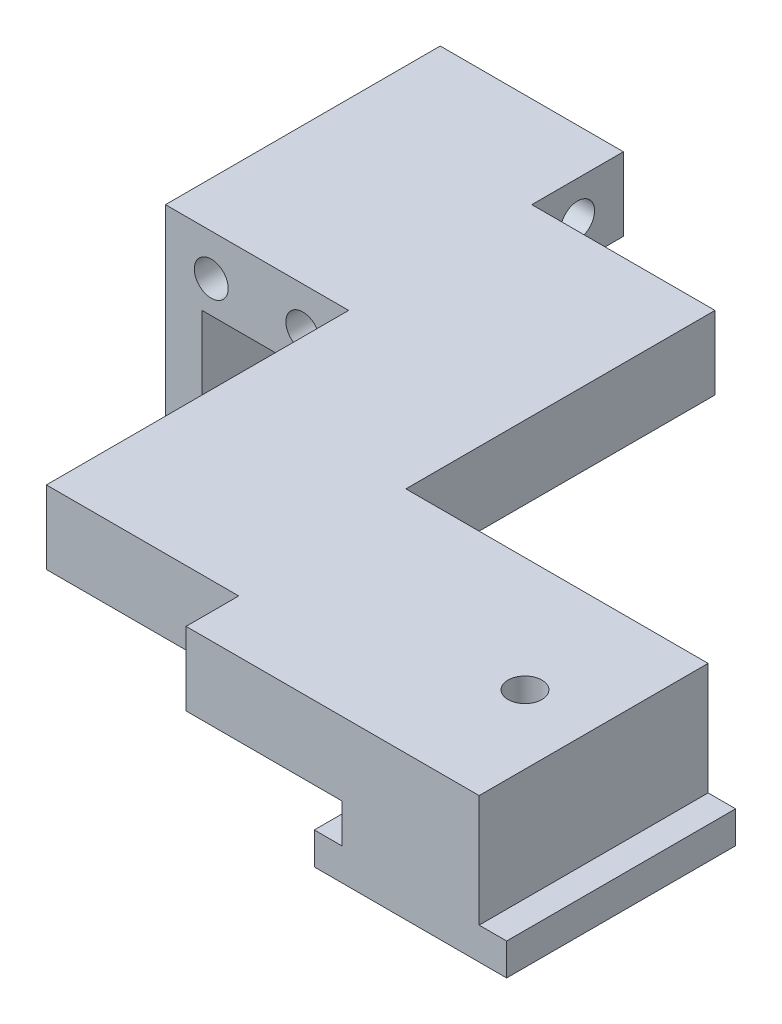
SolidWorks part; units mm, degrees
ref_plane "Front Plane" through (0, 0, 0) normal (0, 0, 1) x (1, 0, 0)
ref_plane "Top Plane" through (0, 0, 0) normal (0, 1, 0) x (1, 0, 0)
ref_plane "Right Plane" through (0, 0, 0) normal (1, 0, 0) x (0, 0, -1)
sketch "Sketch1" plane through (0, 0, 0) normal (0, 0, 1) x (1, 0, 0)
  line L0 (-10.5, 0) -> (10.5, 0)
  line L1 (10.5, 0) -> (10.5, 3.5)
  line L2 (10.5, 3.5) -> (7.5, 3.5)
  line L3 (7.5, 3.5) -> (7.5, 15.75)
  line L4 (7.5, 15.75) -> (-7.5, 15.75)
  line L5 (-7.5, 15.75) -> (-7.5, 3.5)
  line L6 (-7.5, 3.5) -> (-10.5, 3.5)
  line L7 (-10.5, 3.5) -> (-10.5, 0)
  dimension "D1" = 21
  dimension "D2" = 3.5
  dimension "D3" = 3
  dimension "D4" = 12.25
extrude "Boss-Extrude1" add sketch "Sketch1" along normal mid plane 25
sketch "Sketch2" plane through (-7.5, 0, 0) normal (-1, 0, 0) x (0, 0, 1)
  line L0 (12.5, 15.75) -> (12.5, 3.5) construction
  line L1 (-12.5, 15.75) -> (12.5, 15.75)
  line L2 (-12.5, 15.75) -> (-12.5, 7.75)
  line L3 (-12.5, 7.75) -> (12.5, 7.75)
  line L4 (12.5, 15.75) -> (12.5, 7.75)
  dimension "D1" = 8
extrude "Boss-Extrude2" add sketch "Sketch2" along normal blind 38
sketch "Sketch7" plane through (0, 0, -12.5) normal (0, 0, -1) x (-1, 0, 0)
  line L0 (-7.5, 15.75) -> (45.5, 15.75) construction
  line L1 (25.5, 15.75) -> (45.5, 15.75)
  line L2 (25.5, 15.75) -> (25.5, 7.75)
  line L3 (25.5, 7.75) -> (45.5, 7.75)
  line L4 (45.5, 15.75) -> (45.5, 7.75)
  line L5 (45.5, 7.75) -> (7.5, 7.75) construction
  line L7 (45.5, 15.75) -> (45.5, 7.75) construction
  dimension "D2" = 20
extrude "Boss-Extrude3" add sketch "Sketch7" along normal blind 33.75
sketch "Sketch10" plane through (-45.5, 0, 0) normal (-1, 0, 0) x (0, 0, 1)
  line L0 (-46.25, 7.75) -> (12.5, 7.75) construction
  line L1 (-46.25, 15.75) -> (-26.25, 15.75)
  line L2 (-46.25, 15.75) -> (-46.25, 7.75)
  line L3 (-46.25, 7.75) -> (-26.25, 7.75)
  line L4 (-26.25, 15.75) -> (-26.25, 7.75)
  dimension "D1" = 20
extrude "Boss-Extrude4" add sketch "Sketch10" along normal blind 20
sketch "Sketch11" plane through (0, 0, -46.25) normal (0, 0, -1) x (-1, 0, 0)
  line L0 (65.5, 15.75) -> (25.5, 15.75) construction
  line L1 (65.5, 7.75) -> (45.5, 7.75)
  line L2 (65.5, 7.75) -> (65.5, 15.75)
  line L3 (65.5, 15.75) -> (45.5, 15.75)
  line L4 (45.5, 7.75) -> (45.5, 15.75)
  line L6 (45.5, 7.75) -> (45.5, 15.75) construction
extrude "Boss-Extrude5" add sketch "Sketch11" along normal blind 10
hole_wizard "Ø3.7 (3.7) Diameter Hole2" positions "Sketch3" profile "Sketch4" hole size "Ø3.7" standard "ANSI Metric"
sketch "Sketch3" plane through (0, 0, -26.25) normal (0, 0, 1) x (1, 0, 0)
  point P0 (-60.5, 11.25)
  point P2 (-50.5, 11.25)
sketch "Sketch4" plane through (-60.5, 11.25, -26.25) normal (1, 0, 0) x (0, -1, 0)
  line L0 (0, 0) -> (0, 11.1116)
  line L1 (0, 11.1116) -> (1.85, 10)
  line L2 (1.85, 10) -> (1.85, 0)
  line L5 (1.85, 0) -> (0, 0)
  line L10 (0, 11.1116) -> (-1.85, 10) construction
  line L11 (0, -6.35) -> (0, 107.95) construction
  dimension "Hole Dia." = 3.7
  dimension "Hole Depth" = 10
  dimension "Drill Angle" = 118
hole_wizard "Ø3.7 (3.7) Diameter Hole1" positions "Sketch8" profile "Sketch9" hole size "Ø3.7" standard "ANSI Metric" end condition through all
sketch "Sketch8" plane through (-65.5, 0, 0) normal (-1, 0, 0) x (0, 0, 1)
  line L0 (-56.25, 11.75) -> (-51.25, 11.75) construction
  line L2 (-56.25, 7.75) -> (-56.25, 15.75) construction
  point P0 (-51.25, 11.75)
  dimension "D1" = 5
sketch "Sketch9" plane through (-65.5, 11.75, -51.25) normal (0, 1, 0) x (0, 0, 1)
  line L0 (0, 0) -> (0, 76)
  line L1 (0, 76) -> (1.85, 76)
  line L2 (1.85, 76) -> (1.85, 0)
  line L5 (1.85, 0) -> (0, 0)
  line L11 (0, -6.35) -> (0, 107.95) construction
  dimension "Thru Hole Dia." = 3.7
  dimension "Thru Hole Depth" = 76
hole_wizard "Ø3.7 (3.7) Diameter Hole3" positions "Sketch5" profile "Sketch6" hole size "Ø3.7" standard "ANSI Metric" end condition through all
sketch "Sketch5" plane through (0, 15.75, 0) normal (0, 1, 0) x (1, 0, 0)
  line L2 (0, 0) -> (7.5, 0) construction
  line L3 (7.5, -12.5) -> (7.5, 12.5) construction
  point P0 (0, 0)
sketch "Sketch6" plane through (0, 15.75, 0) normal (1, 0, 0) x (0, 0, 1)
  line L0 (0, 0) -> (0, 15.75)
  line L1 (0, 15.75) -> (1.85, 15.75)
  line L2 (1.85, 15.75) -> (1.85, 0)
  line L5 (1.85, 0) -> (0, 0)
  line L11 (0, -6.35) -> (0, 107.95) construction
  dimension "Thru Hole Dia." = 3.7
  dimension "Thru Hole Depth" = 15.75
sketch "Sketch12" plane through (0, 15.75, 0) normal (0, 1, 0) x (1, 0, 0)
  line L1 (-45.5, -12.5) -> (-24.5, -12.5)
  line L2 (-45.5, -12.5) -> (-45.5, -6.75)
  line L3 (-45.5, -6.75) -> (-24.5, -6.75)
  line L4 (-24.5, -12.5) -> (-24.5, -6.75)
  dimension "D1" = 21
  dimension "D2" = 5.75
extrude "Cut-Extrude1" cut sketch "Sketch12" against normal through all
sketch "Sketch14" plane through (0, 7.75, 0) normal (0, -1, 0) x (1, 0, 0)
  line L0 (-65.5, -26.25) -> (-45.5, -26.25) construction
  line L1 (-65.5, -56.25) -> (-61.5, -56.25)
  line L2 (-65.5, -56.25) -> (-65.5, -26.25)
  line L3 (-65.5, -26.25) -> (-61.5, -26.25)
  line L4 (-61.5, -56.25) -> (-61.5, -26.25)
  dimension "D1" = 4
extrude "Boss-Extrude7" add sketch "Sketch14" along normal blind 15.5
sketch "Sketch15" plane through (-61.5, 0, 0) normal (1, 0, 0) x (0, 0, -1)
  line L0 (56.25, -7.75) -> (56.25, 7.75) construction
  line L1 (26.25, -7.75) -> (56.25, -7.75)
  line L2 (26.25, -7.75) -> (26.25, -5.5)
  line L3 (26.25, -5.5) -> (56.25, -5.5)
  line L4 (56.25, -7.75) -> (56.25, -5.5)
  dimension "D1" = 2.25
extrude "Boss-Extrude8" add sketch "Sketch15" along normal blind 5
